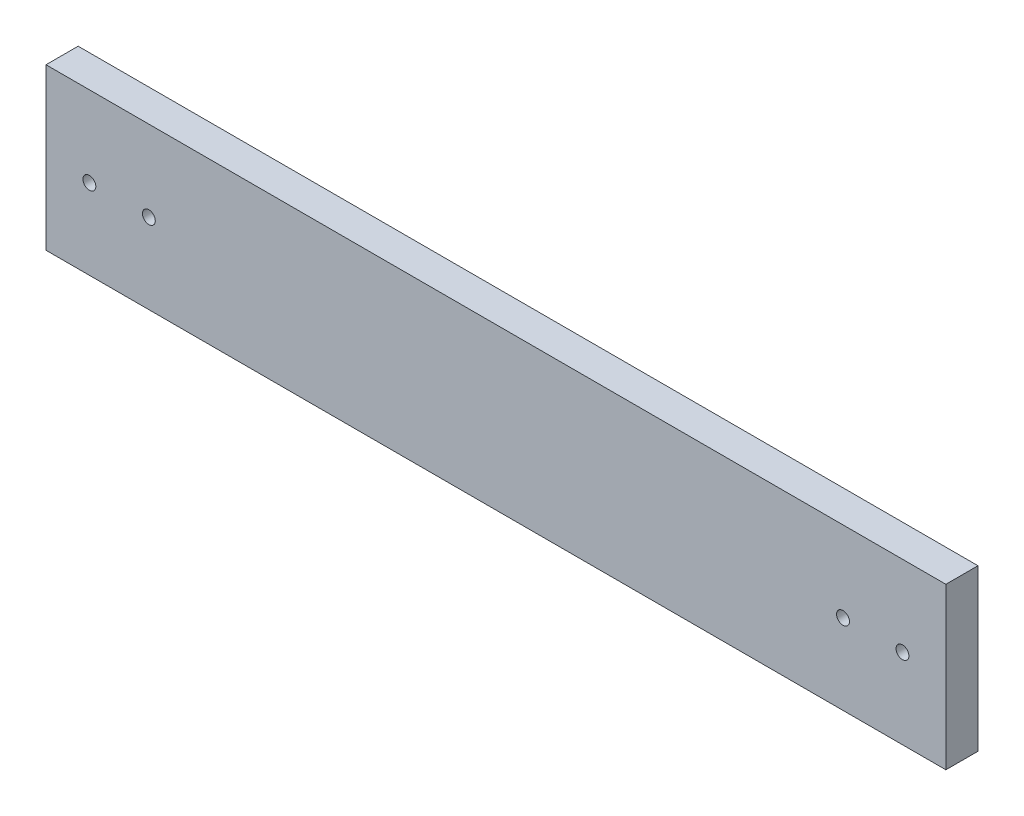
SolidWorks part; units mm, degrees
material "Multistrato di pioppo"
ref_plane "Piano frontale" through (0, 0, 0) normal (0, 0, 1) x (1, 0, 0)
ref_plane "Piano superiore" through (0, 0, 0) normal (0, 1, 0) x (1, 0, 0)
ref_plane "Piano destro" through (0, 0, 0) normal (1, 0, 0) x (0, 0, -1)
sketch "Schizzo1" plane through (0, 0, 0) normal (0, 0, 1) x (1, 0, 0)
  line L1 (0, 0) -> (-280, 0)
  line L2 (0, 0) -> (0, 50)
  line L3 (0, 50) -> (-280, 50)
  line L4 (-280, 0) -> (-280, 50)
  dimension "D1" = 280
  dimension "D2" = 50
extrude "Estrusione-Estrusione1" add sketch "Schizzo1" along normal blind 10
sketch "Schizzo2" plane through (0, 0, 0) normal (0, 0, -1) x (-1, 0, 0)
  circle A0 centre (248, 24.9337) radius 2
  circle A1 centre (266.5, 24.9337) radius 2
  circle A2 centre (13.5, 24.9337) radius 2
  circle A3 centre (32, 24.9337) radius 2
  dimension "D1" = 4
extrude "Taglio-Estrusione1" cut sketch "Schizzo2" against normal blind 10
